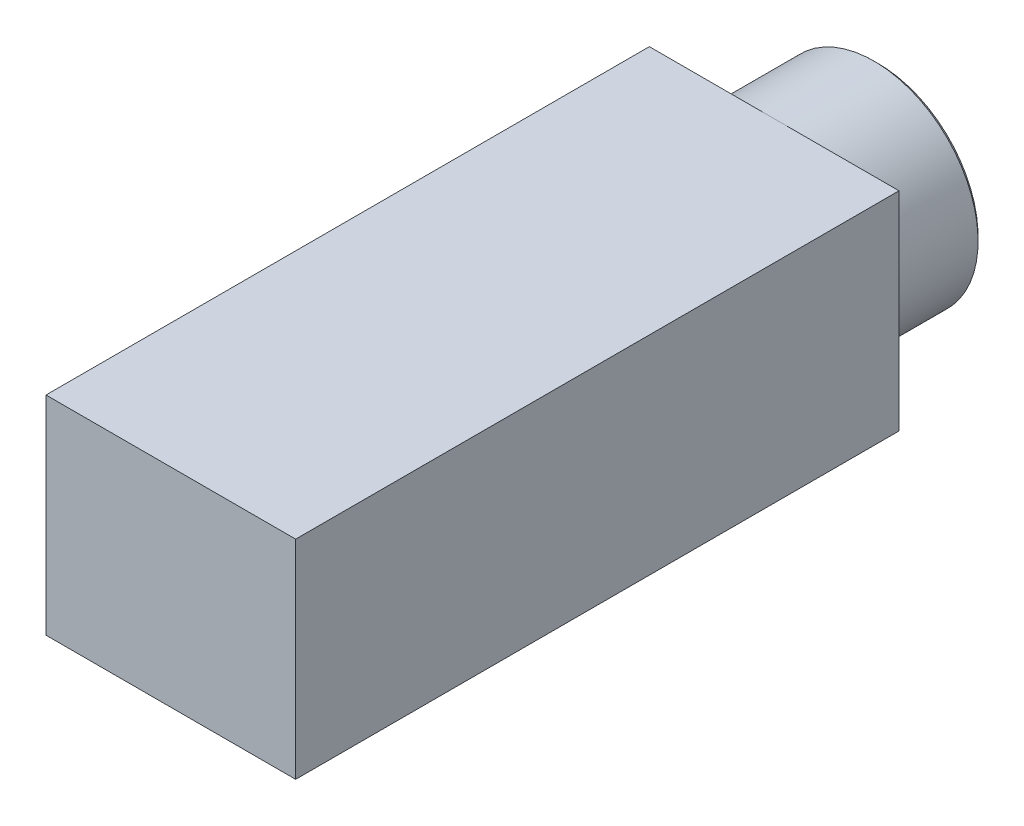
SolidWorks part; units mm, degrees
ref_plane "Front Plane" through (0, 0, 0) normal (0, 0, 1) x (1, 0, 0)
ref_plane "Top Plane" through (0, 0, 0) normal (0, 1, 0) x (1, 0, 0)
ref_plane "Right Plane" through (0, 0, 0) normal (1, 0, 0) x (0, 0, -1)
sketch "Sketch1" plane through (0, 0, 0) normal (0, 0, 1) x (1, 0, 0)
  line L1 (3, -2.5) -> (-3, -2.5)
  line L2 (3, -2.5) -> (3, 2.5)
  line L3 (3, 2.5) -> (-3, 2.5)
  line L4 (-3, -2.5) -> (-3, 2.5)
  line L5 (3, -2.5) -> (-3, 2.5) construction
  line L6 (3, 2.5) -> (-3, -2.5) construction
  point P0 (0, 0)
  dimension "D1" = 6
  dimension "D2" = 5
extrude "Boss-Extrude1" add sketch "Sketch1" along normal blind 14.5
sketch "Sketch2" plane through (0, 0, 0) normal (0, 0, -1) x (-1, 0, 0)
  circle A0 centre (0, 0) radius 2.5
extrude "Boss-Extrude2" add sketch "Sketch2" along normal blind 2.5
sketch "Sketch3" plane through (0, 0, -2.5) normal (0, 0, -1) x (-1, 0, 0)
  circle A0 centre (0, 0) radius 1.8
  dimension "D1" = 3.6
extrude "Cut-Extrude1" cut sketch "Sketch3" against normal blind 2.5
chamfer "Chamfer1" distance 0.1 angle 45 1 edges at (-2.5, 0, -2.5)
